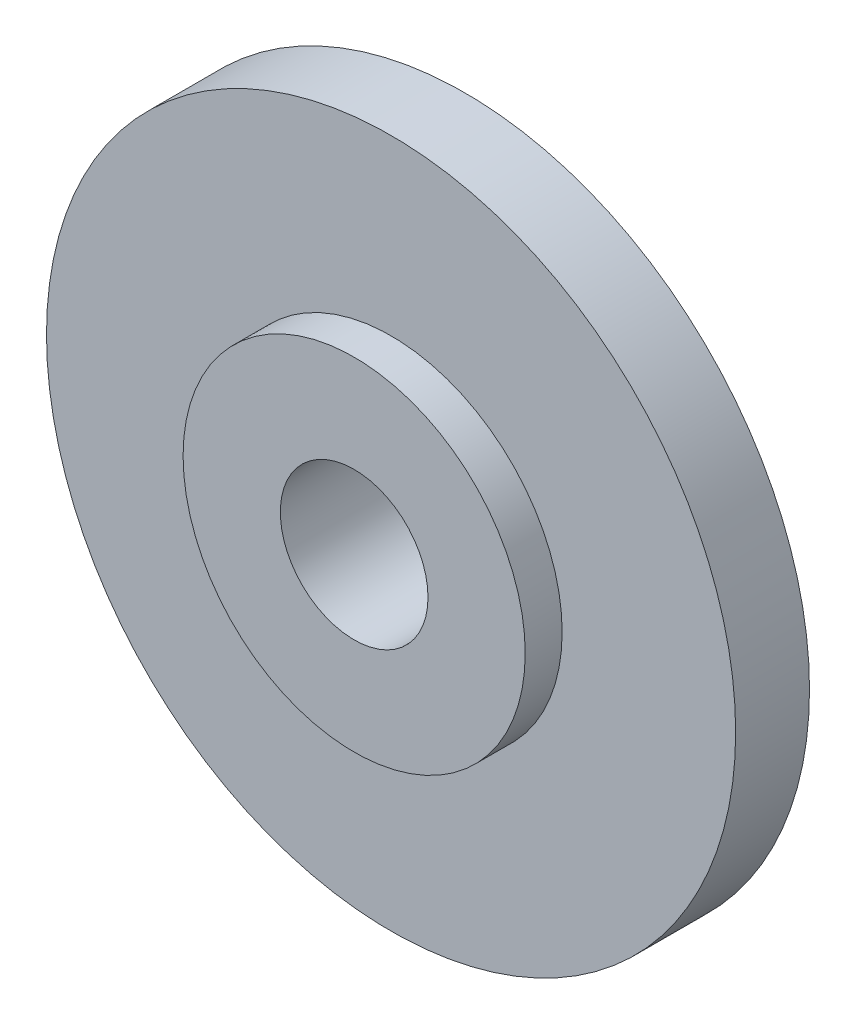
SolidWorks part; units mm, degrees
ref_plane "Front Plane" through (0, 0, 0) normal (0, 0, 1) x (1, 0, 0)
ref_plane "Top Plane" through (0, 0, 0) normal (0, 1, 0) x (1, 0, 0)
ref_plane "Right Plane" through (0, 0, 0) normal (1, 0, 0) x (0, 0, -1)
sketch "Sketch1" plane through (0, 0, 0) normal (0, 0, 1) x (1, 0, 0)
  circle A0 centre (0, 0) radius 14
extrude "Boss-Extrude1" add sketch "Sketch1" along normal blind 3
sketch "Sketch2" plane through (0, 0, 3) normal (0, 0, 1) x (1, 0, 0)
  circle A0 centre (0, 0) radius 6.95
extrude "Boss-Extrude2" add sketch "Sketch2" along normal blind 1.5
sketch "Sketch3" plane through (0, 0, 4.5) normal (0, 0, 1) x (1, 0, 0)
  circle A0 centre (0, 0) radius 3
extrude "Cut-Extrude1" cut sketch "Sketch3" against normal through all
